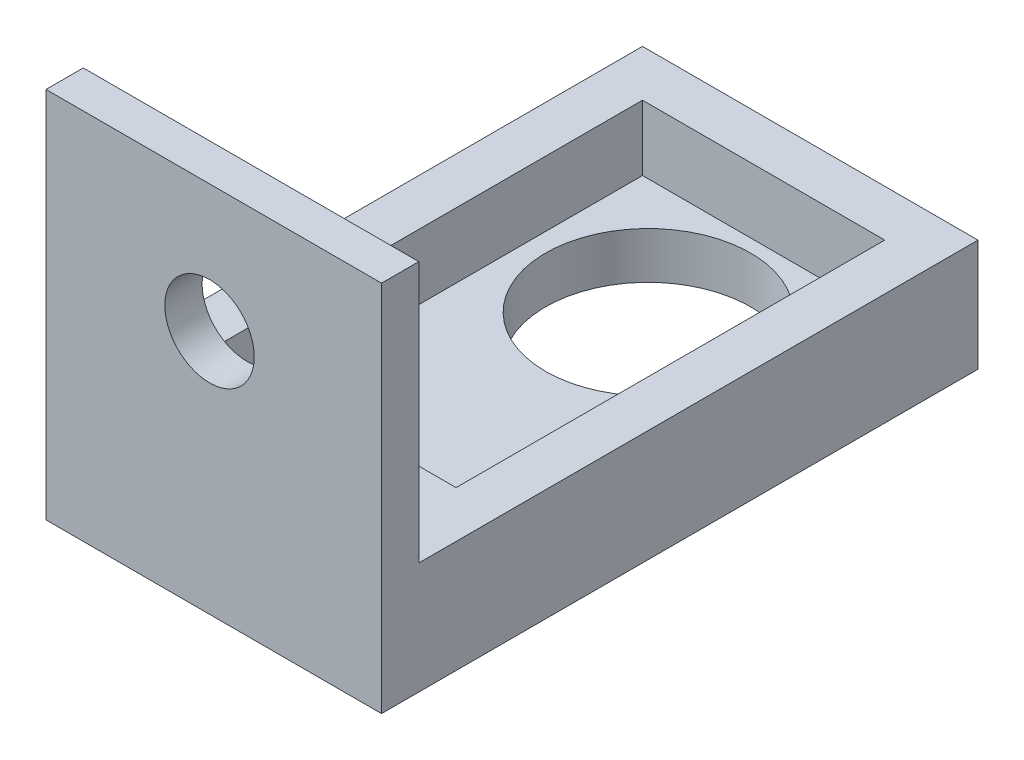
SolidWorks part; units mm, degrees
ref_plane "Front Plane" through (0, 0, 0) normal (0, 0, 1) x (1, 0, 0)
ref_plane "Top Plane" through (0, 0, 0) normal (0, 1, 0) x (1, 0, 0)
ref_plane "Right Plane" through (0, 0, 0) normal (1, 0, 0) x (0, 0, -1)
sketch "Sketch1" plane through (0, 0, 0) normal (0, 1, 0) x (1, 0, 0)
  line L1 (0, 0) -> (18, 0)
  line L2 (0, 0) -> (0, 32)
  line L3 (0, 32) -> (18, 32)
  line L4 (18, 0) -> (18, 32)
  dimension "D1" = 18
  dimension "D2" = 32
extrude "Boss-Extrude1" add sketch "Sketch1" along normal blind 6 contours L2 L3 L4 L1
sketch "Sketch2" plane through (0, 6, 0) normal (0, 1, 0) x (1, 0, 0)
  line L0 (0, 0) -> (0, 32) construction
  line L1 (2.5, 29.5) -> (15.5, 29.5)
  line L2 (2.5, 29.5) -> (2.5, 6.5)
  line L3 (2.5, 6.5) -> (15.5, 6.5)
  line L4 (15.5, 29.5) -> (15.5, 6.5)
  line L5 (0, 0) -> (18, 0) construction
  dimension "D1" = 13
  dimension "D2" = 23
  dimension "D3" = 2.5
  dimension "D4" = 6.5
extrude "Cut-Extrude1" cut sketch "Sketch2" against normal blind 3.5
sketch "Sketch3" plane through (0, 2.5, 0) normal (0, 1, 0) x (1, 0, 0)
  line L0 (15.5, 29.5) -> (2.5, 29.5) construction
  circle A0 centre (9.0008, 23.3) radius 5.5
  point P2 (9.0008, 18.8607)
  dimension "D1" = 6.2
extrude "Cut-Extrude2" cut sketch "Sketch3" against normal through all
sketch "Sketch4" plane through (0, 6, 0) normal (0, 1, 0) x (1, 0, 0)
  line L0 (0, 0) -> (0, 32) construction
  line L1 (0, 2) -> (18, 2)
  line L2 (0, 2) -> (0, 0)
  line L3 (0, 0) -> (18, 0)
  line L4 (18, 2) -> (18, 0)
  dimension "D1" = 2
extrude "Boss-Extrude2" add sketch "Sketch4" along normal blind 14
sketch "Sketch5" plane through (0, 0, -2) normal (0, 0, -1) x (-1, 0, 0)
  circle A0 centre (-8.7742, 13.1552) radius 2.4
  circle A1 centre (-3.7583, 13.1552) radius 1
  circle A2 centre (-13.7901, 13.1552) radius 1
extrude "Cut-Extrude3" cut sketch "Sketch5" against normal through all contours A0
